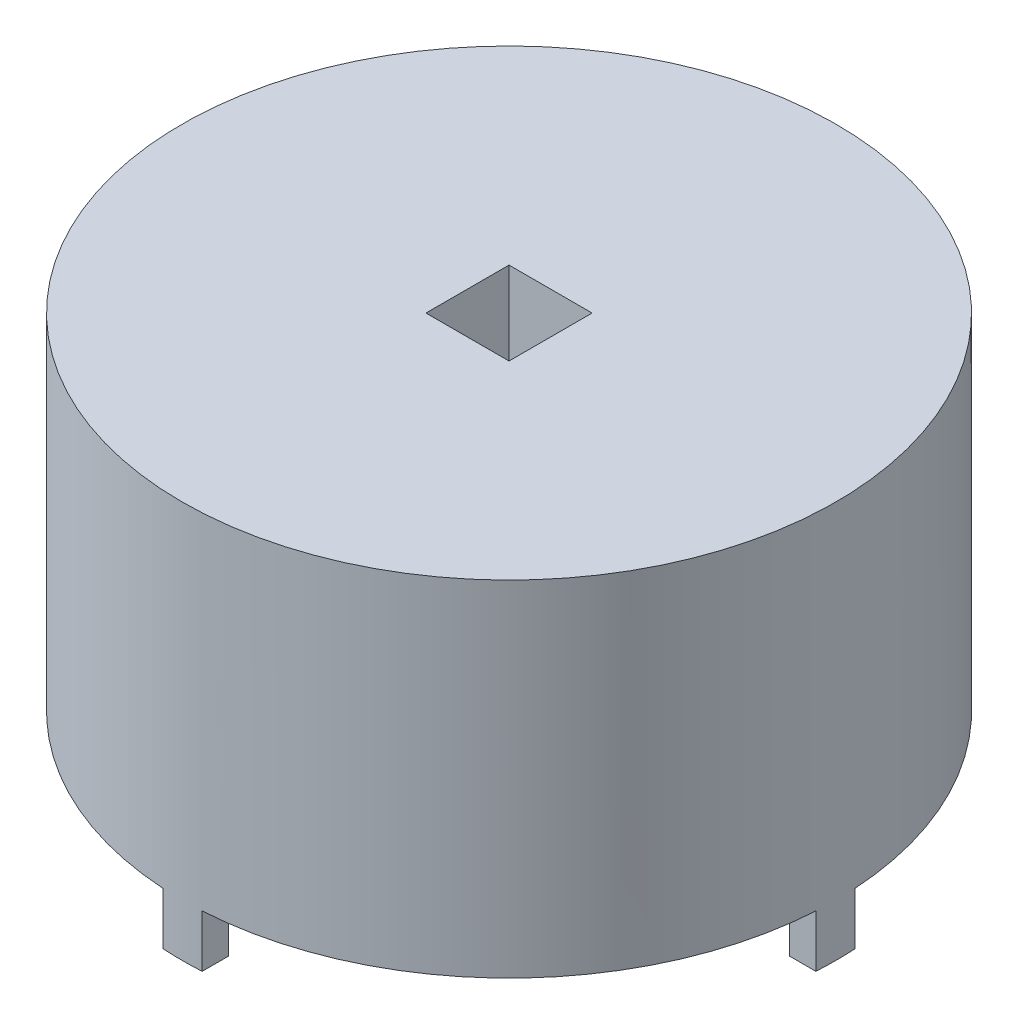
SolidWorks part; units mm, degrees
ref_plane "Front Plane" through (0, 0, 0) normal (0, 0, 1) x (1, 0, 0)
ref_plane "Top Plane" through (0, 0, 0) normal (0, 1, 0) x (1, 0, 0)
ref_plane "Right Plane" through (0, 0, 0) normal (1, 0, 0) x (0, 0, -1)
sketch "Sketch1" plane through (0, 0, 0) normal (0, 1, 0) x (1, 0, 0)
  circle A0 centre (0, 0) radius 23
  circle A1 centre (0, 0) radius 25
  dimension "D1" = 46
  dimension "D2" = 50
extrude "Boss-Extrude1" add sketch "Sketch1" along normal mid plane 20
sketch "Sketch2" plane through (0, -10, 0) normal (0, -1, 0) x (1, 0, 0)
  line L0 (22.951, -1.5) -> (25, -1.5)
  line L1 (-1.5, 22.951) -> (1.5, 22.951)
  line L2 (-1.5, 22.951) -> (-1.5, 25)
  line L3 (-1.5, 25) -> (1.5, 25)
  line L4 (1.5, 22.951) -> (1.5, 25)
  line L5 (25, 1.5) -> (25, -1.5)
  line L6 (22.951, 1.5) -> (25, 1.5)
  line L7 (22.951, 1.5) -> (22.951, -1.5)
  line L8 (-1.5, -22.951) -> (-1.5, -25)
  line L9 (1.5, -25) -> (-1.5, -25)
  line L10 (1.5, -22.951) -> (1.5, -25)
  line L11 (1.5, -22.951) -> (-1.5, -22.951)
  line L12 (-22.951, 1.5) -> (-25, 1.5)
  line L13 (-25, -1.5) -> (-25, 1.5)
  line L14 (-22.951, -1.5) -> (-25, -1.5)
  line L15 (-22.951, -1.5) -> (-22.951, 1.5)
  circle A3 centre (0, 0) radius 23 construction
  circle A4 centre (0, 0) radius 25
  circle A5 centre (0, 0) radius 25
  point P11 (0, 25)
  point P25 (0, 0)
  dimension "D2" = 3
  dimension "D3" = 4
extrude "Boss-Extrude2" add sketch "Sketch2" along normal blind 4
sketch "Sketch3" plane through (0, 10, 0) normal (0, 1, 0) x (1, 0, 0)
  line L1 (-3.175, -3.175) -> (3.175, -3.175)
  line L2 (-3.175, -3.175) -> (-3.175, 3.175)
  line L3 (-3.175, 3.175) -> (3.175, 3.175)
  line L4 (3.175, -3.175) -> (3.175, 3.175)
  line L5 (-3.175, -3.175) -> (3.175, 3.175) construction
  line L6 (-3.175, 3.175) -> (3.175, -3.175) construction
  circle A3 centre (0, 0) radius 25
  circle A4 centre (0, 0) radius 25
  dimension "D2" = 6.35
extrude "Boss-Extrude3" add sketch "Sketch3" along normal blind 6.35
fillet "Fillet1" [suppressed] radius 1.3333
equation "\"InnerDiameter\" = 46"
equation "\"D1@Sketch1\"=\"InnerDiameter\""
equation "\"OuterDiameter\" = 50"
equation "\"D2@Sketch1\"=\"OuterDiameter\""
equation "\"Depth\" = 20mm"
equation "\"D1@Boss-Extrude1\"=\"Depth\""
equation "\"GapWidth\" = 3mm"
equation "\"D2@Sketch2\"=\"GapWidth\""
equation "\"PegDepth\" = 4mm"
equation "\"D1@Boss-Extrude2\"=\"PegDepth\""
equation "\"SocketSize\"= 1in / 4"
equation "\"D2@Sketch3\"=\"SocketSize\""
equation "\"SocketToolDepth\"= 1in / 4"
equation "\"D1@Boss-Extrude3\"=\"SocketToolDepth\""
equation "\"D1@Fillet1\"=\"PegDepth\"/3"
